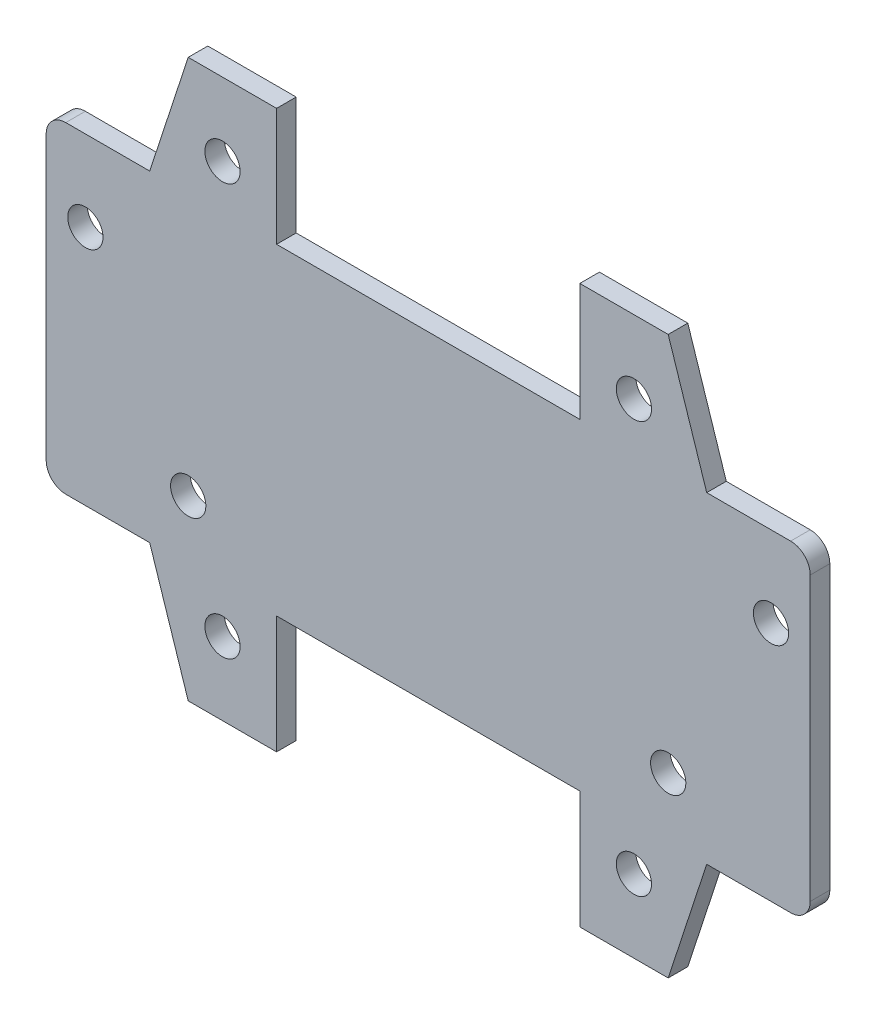
SolidWorks part; units mm, degrees
ref_plane "前视基准面" through (0, 0, 0) normal (0, 0, 1) x (1, 0, 0)
ref_plane "上视基准面" through (0, 0, 0) normal (0, 1, 0) x (1, 0, 0)
ref_plane "右视基准面" through (0, 0, 0) normal (1, 0, 0) x (0, 0, -1)
sketch "草图1" plane through (0, 0, 0) normal (0, 0, 1) x (1, 0, 0)
  line L0 (0, 0) -> (0, 16.4286) construction
  line L1 (39, -16.4286) -> (28.4306, -16.4286)
  line L2 (39, -16.4286) -> (39, 16.4286)
  line L3 (39, 16.4286) -> (28.4306, 16.4286)
  line L4 (-39, -16.4286) -> (-39, 16.4286)
  line L5 (39, -16.4286) -> (24.5, -10.3205) construction
  line L6 (39, 16.4286) -> (-39, -16.4286) construction
  line L9 (22.8412, -9.6217) -> (-39, 16.4286) construction
  line L11 (33.2, 8.1795) -> (35, 8.1795)
  line L12 (0, 0) -> (-39, 0) construction
  line L13 (-21, 21) -> (21, 21) construction
  line L14 (-21, 21) -> (-21, -10.3205) construction
  line L15 (-21, -21) -> (21, -21) construction
  line L16 (21, 21) -> (21, -21) construction
  line L17 (-21, 21) -> (21, -21) construction
  line L18 (-21, -21) -> (-19.7272, -19.7272) construction
  line L19 (-28.4306, 16.4286) -> (-24.5, 28.449)
  line L20 (-24.5, 28.449) -> (-15.4785, 28.449)
  line L21 (-15.4785, 28.449) -> (-15.4785, 16.4286)
  line L22 (-28.4306, 16.4286) -> (-39, 16.4286)
  line L23 (28.4306, 16.4286) -> (24.5, 28.449)
  line L24 (24.5, 28.449) -> (15.4785, 28.449)
  line L25 (15.4785, 28.449) -> (15.4785, 16.4286)
  line L26 (15.4785, 16.4286) -> (-15.4785, 16.4286)
  line L27 (28.4306, -16.4286) -> (24.5, -28.449)
  line L28 (24.5, -28.449) -> (15.4785, -28.449)
  line L29 (15.4785, -28.449) -> (15.4785, -16.4286)
  line L30 (-24.5, -28.449) -> (-15.4785, -28.449)
  line L31 (-28.4306, -16.4286) -> (-24.5, -28.449)
  line L32 (-15.4785, -28.449) -> (-15.4785, -16.4286)
  line L33 (-28.4306, -16.4286) -> (-39, -16.4286)
  line L34 (-21, -19.2) -> (-21, -21) construction
  line L35 (-10.3205, -10.3205) -> (21, 21) construction
  line L36 (15.4785, -16.4286) -> (-15.4785, -16.4286)
  circle A0 centre (24.5, -10.3205) radius 1.8
  circle A1 centre (-24.5, -10.3205) radius 1.8
  circle A2 centre (35, 8.1795) radius 1.8
  circle A3 centre (-35, 8.1795) radius 1.8
  circle A4 centre (21, 21) radius 1.8
  circle A5 centre (-21, 21) radius 1.8
  circle A6 centre (-21, -21) radius 1.8
  circle A7 centre (21, -21) radius 1.8
  point P0 (0, 0)
  point P19 (0, 0)
  point P38 (19.9892, 28.449)
  point P41 (19.9892, -28.449)
  dimension "D2" = 3.6
  dimension "D3" = 3.6
  dimension "D5" = 3.6
  dimension "D8" = 42
  dimension "D10" = 3.6
  dimension "D1" = 78
  dimension "D4" = 49
  dimension "D9" = 42
extrude "凸台-拉伸1" add sketch "草图1" along normal blind 2 contours L36 L29 L28 L27 L1 L2 L3 L23 L24 L25 L26 L21 L20 L19 L22 L4 L33 L31 L30 L32 A5 A4 A0 A1 A2 A3 A6 A7
fillet "圆角1" radius 2 4 edges at (39, 16.4286, 1) (39, -16.4286, 1) (-39, -16.4286, 1) (-39, 16.4286, 1)
